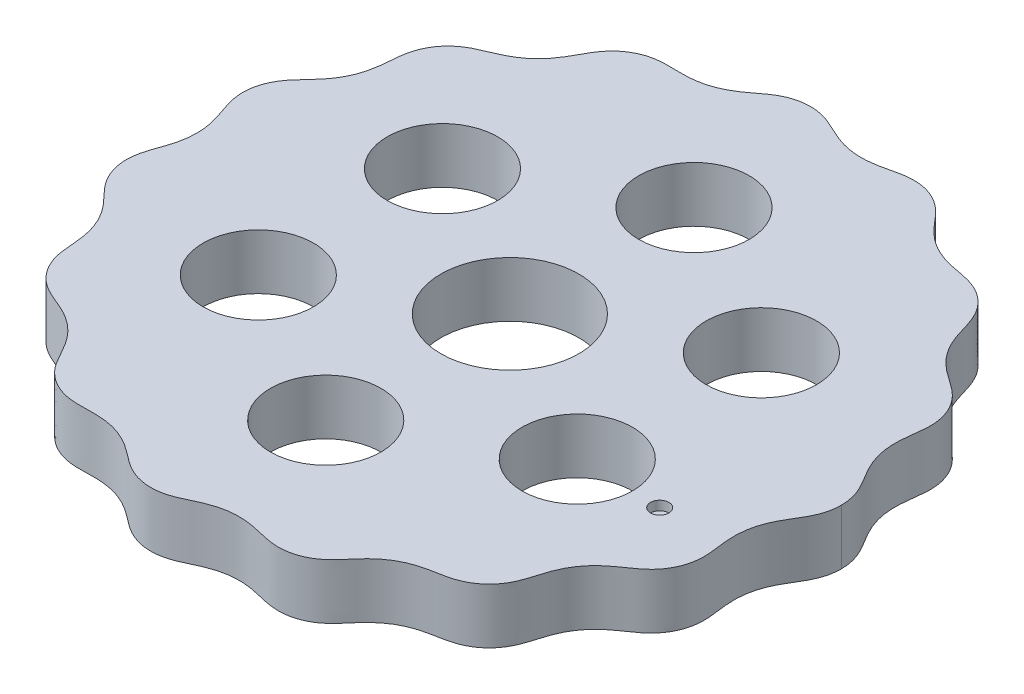
SolidWorks part; units mm, degrees
ref_plane "Front Plane" through (0, 0, 0) normal (0, 0, 1) x (1, 0, 0)
ref_plane "Top Plane" through (0, 0, 0) normal (0, 1, 0) x (1, 0, 0)
ref_plane "Right Plane" through (0, 0, 0) normal (1, 0, 0) x (0, 0, -1)
sketch "Sketch3" plane through (0, 0, 0) normal (0, 1, 0) x (1, 0, 0)
  line L0 (-55, 0) -> (55, 0) construction
  spline S2 degree 4 poles (-35, 0) (-35, -0.0358) (-35.0006, -0.1075) (-35.0034, -0.2568) (-35.0108, -0.4216) (-35.0218, -0.5882) (-35.0365, -0.7567) (-35.0593, -0.9658) (-35.104, -1.2906) (-35.1852, -1.7284) (-35.3211, -2.2743) (-35.5114, -2.8829) (-35.7441, -3.5419) (-35.9992, -4.258) (-36.256, -5.1614) (-36.3903, -6.2748) (-36.277, -7.5121) (-35.8687, -8.6952) (-35.2773, -9.6694) (-34.5543, -10.5199) (-33.7836, -11.2989) (-32.9858, -12.2016) (-32.2646, -13.303) (-31.7377, -14.5286) (-31.4262, -15.8454) (-31.2991, -17.2726) (-31.2161, -18.7053) (-30.8161, -20.1006) (-30.0732, -21.3418) (-29.1744, -22.2504) (-28.1724, -22.8961) (-27.1276, -23.3559) (-26.1086, -23.7587) (-25.0498, -24.278) (-23.9897, -24.9979) (-23.0387, -25.9222) (-22.2349, -27.0329) (-21.57, -28.2819) (-20.9001, -29.5134) (-19.9625, -30.5741) (-18.7952, -31.3663) (-17.5956, -31.8107) (-16.4147, -31.9743) (-15.2812, -31.959) (-14.2035, -31.9175) (-13.0422, -31.968) (-11.7833, -32.2012) (-10.5313, -32.6697) (-9.484, -33.2925) (-8.6483, -33.9206) (-7.824, -34.5602) (-6.9633, -35.1551) (-5.8447, -35.655) (-4.4715, -35.8938) (-3.1871, -35.8055) (-2.026, -35.4617) (-0.9923, -34.9762) (-0.0227, -34.5029) (1.0531, -34.0876) (2.2996, -33.7945) (3.6433, -33.7224) (5.0385, -33.8989) (6.246, -34.2125) (7.2644, -34.4441) (8.3052, -34.5433) (9.3521, -34.4822) (10.5168, -34.1673) (11.6593, -33.5372) (12.5907, -32.7091) (13.341, -31.8149) (14.0543, -30.9824) (14.885, -30.183) (15.9219, -29.4318) (16.9904, -28.9178) (18.0263, -28.6023) (18.918, -28.4136) (19.5788, -28.294) (20.4038, -28.1355) (21.3777, -27.8617) (22.444, -27.3351) (23.4837, -26.4602) (24.2541, -25.4059) (24.7506, -24.2626) (25.0639, -23.1466) (25.3786, -22.114) (25.8131, -21.0649) (26.4604, -19.9607) (27.3438, -18.9326) (28.3229, -18.1436) (29.2182, -17.5418) (30.0287, -16.9727) (30.7971, -16.3286) (31.5499, -15.4136) (32.138, -14.1887) (32.4089, -12.902) (32.389, -11.6377) (32.2136, -10.4744) (32.0853, -9.3852) (32.0701, -8.4106) (32.1519, -7.5639) (32.3146, -6.756) (32.5488, -5.9926) (32.8579, -5.2665) (33.2246, -4.5794) (33.5887, -3.9735) (33.9236, -3.4333) (34.2476, -2.8753) (34.5352, -2.2866) (34.722, -1.7814) (34.8335, -1.3753) (34.8947, -1.0872) (34.9248, -0.9216) (34.9499, -0.7552) (34.9676, -0.6083) (34.9796, -0.4838) (34.9875, -0.3802) (34.9925, -0.2949) (34.9973, -0.1832) (34.9994, -0.0895) (35, -0.0358) (35, 0) knots 0.07237 0.07237 0.07237 0.07237 0.07237 0.073615 0.074861 0.076106 0.077352 0.078597 0.079843 0.082334 0.087049 0.091763 0.096478 0.101193 0.107725 0.114257 0.124215 0.134174 0.144133 0.15093 0.157727 0.167143 0.176558 0.186521 0.196482 0.206428 0.216375 0.228908 0.238867 0.248826 0.258784 0.266347 0.27391 0.282559 0.291208 0.301173 0.311645 0.3216 0.331555 0.343059 0.353018 0.362977 0.372935 0.380513 0.388091 0.396475 0.404859 0.414823 0.425824 0.43578 0.440758 0.445737 0.45671 0.466668 0.476627 0.486585 0.494428 0.502271 0.510391 0.51851 0.528475 0.540003 0.54996 0.559918 0.565389 0.570861 0.580819 0.590778 0.600736 0.609095 0.617453 0.625308 0.633162 0.643126 0.655188 0.660155 0.665121 0.670088 0.675054 0.685012 0.69497 0.704929 0.714887 0.72326 0.731632 0.739222 0.746812 0.756777 0.769366 0.779036 0.78387 0.788705 0.798662 0.808621 0.81858 0.828538 0.837175 0.845812 0.853389 0.860965 0.865947 0.870929 0.877739 0.88455 0.889251 0.893953 0.898654 0.903356 0.908335 0.913314 0.914559 0.915803 0.917048 0.918293 0.919538 0.92016 0.920783 0.921405 0.922028 0.923272 0.923272 0.923272 0.923272 0.923272
  spline S3 degree 4 poles (-35, 0) (-35, 0.0358) (-35.0006, 0.1075) (-35.0034, 0.2568) (-35.0108, 0.4216) (-35.0218, 0.5882) (-35.0365, 0.7567) (-35.0593, 0.9658) (-35.104, 1.2906) (-35.1852, 1.7284) (-35.3211, 2.2743) (-35.5114, 2.8829) (-35.7441, 3.5419) (-35.9992, 4.258) (-36.256, 5.1614) (-36.3903, 6.2748) (-36.277, 7.5121) (-35.8687, 8.6952) (-35.2773, 9.6694) (-34.5543, 10.5199) (-33.7836, 11.2989) (-32.9858, 12.2016) (-32.2646, 13.303) (-31.7377, 14.5286) (-31.4262, 15.8454) (-31.2991, 17.2726) (-31.2161, 18.7053) (-30.8161, 20.1006) (-30.0732, 21.3418) (-29.1744, 22.2504) (-28.1724, 22.8961) (-27.1276, 23.3559) (-26.1086, 23.7587) (-25.0498, 24.278) (-23.9897, 24.9979) (-23.0387, 25.9222) (-22.2349, 27.0329) (-21.57, 28.2819) (-20.9001, 29.5134) (-19.9625, 30.5741) (-18.7952, 31.3663) (-17.5956, 31.8107) (-16.4147, 31.9743) (-15.2812, 31.959) (-14.2035, 31.9175) (-13.0422, 31.968) (-11.7833, 32.2012) (-10.5313, 32.6697) (-9.484, 33.2925) (-8.6483, 33.9206) (-7.824, 34.5602) (-6.9633, 35.1551) (-5.8447, 35.655) (-4.4715, 35.8938) (-3.1871, 35.8055) (-2.026, 35.4617) (-0.9923, 34.9762) (-0.0227, 34.5029) (1.0531, 34.0876) (2.2996, 33.7945) (3.6433, 33.7224) (5.0385, 33.8989) (6.246, 34.2125) (7.2644, 34.4441) (8.3052, 34.5433) (9.3521, 34.4822) (10.5168, 34.1673) (11.6593, 33.5372) (12.5907, 32.7091) (13.341, 31.8149) (14.0543, 30.9824) (14.885, 30.183) (15.9219, 29.4318) (16.9904, 28.9178) (18.0263, 28.6023) (18.918, 28.4136) (19.5788, 28.294) (20.4038, 28.1355) (21.3777, 27.8617) (22.444, 27.3351) (23.4837, 26.4602) (24.2541, 25.4059) (24.7506, 24.2626) (25.0639, 23.1466) (25.3786, 22.114) (25.8131, 21.0649) (26.4604, 19.9607) (27.3438, 18.9326) (28.3229, 18.1436) (29.2182, 17.5418) (30.0287, 16.9727) (30.7971, 16.3286) (31.5499, 15.4136) (32.138, 14.1887) (32.4089, 12.902) (32.389, 11.6377) (32.2136, 10.4744) (32.0853, 9.3852) (32.0701, 8.4106) (32.1519, 7.5639) (32.3146, 6.756) (32.5488, 5.9926) (32.8579, 5.2665) (33.2246, 4.5794) (33.5887, 3.9735) (33.9236, 3.4333) (34.2476, 2.8753) (34.5352, 2.2866) (34.722, 1.7814) (34.8335, 1.3753) (34.8947, 1.0872) (34.9248, 0.9216) (34.9499, 0.7552) (34.9676, 0.6083) (34.9796, 0.4838) (34.9875, 0.3802) (34.9925, 0.2949) (34.9973, 0.1832) (34.9994, 0.0895) (35, 0.0358) (35, 0) knots 0.07237 0.07237 0.07237 0.07237 0.07237 0.073615 0.074861 0.076106 0.077352 0.078597 0.079843 0.082334 0.087049 0.091763 0.096478 0.101193 0.107725 0.114257 0.124215 0.134174 0.144133 0.15093 0.157727 0.167143 0.176558 0.186521 0.196482 0.206428 0.216375 0.228908 0.238867 0.248826 0.258784 0.266347 0.27391 0.282559 0.291208 0.301173 0.311645 0.3216 0.331555 0.343059 0.353018 0.362977 0.372935 0.380513 0.388091 0.396475 0.404859 0.414823 0.425824 0.43578 0.440758 0.445737 0.45671 0.466668 0.476627 0.486585 0.494428 0.502271 0.510391 0.51851 0.528475 0.540003 0.54996 0.559918 0.565389 0.570861 0.580819 0.590778 0.600736 0.609095 0.617453 0.625308 0.633162 0.643126 0.655188 0.660155 0.665121 0.670088 0.675054 0.685012 0.69497 0.704929 0.714887 0.72326 0.731632 0.739222 0.746812 0.756777 0.769366 0.779036 0.78387 0.788705 0.798662 0.808621 0.81858 0.828538 0.837175 0.845812 0.853389 0.860965 0.865947 0.870929 0.877739 0.88455 0.889251 0.893953 0.898654 0.903356 0.908335 0.913314 0.914559 0.915803 0.917048 0.918293 0.919538 0.92016 0.920783 0.921405 0.922028 0.923272 0.923272 0.923272 0.923272 0.923272
extrude "Boss-Extrude1" add sketch "Sketch3" along normal blind 6
sketch "Sketch4" plane through (0, 6, 0) normal (0, 1, 0) x (1, 0, 0)
  circle A0 centre (-1, 0) radius 7.5
  circle A1 centre (-1, 0) radius 20 construction
  circle A2 centre (-1, 20) radius 6
  circle A3 centre (16.3205, 10) radius 6
  circle A4 centre (16.3205, -10) radius 6
  circle A5 centre (-1, -20) radius 6
  circle A6 centre (-18.3205, -10) radius 6
  circle A7 centre (-18.3205, 10) radius 6
  point P19 (-1, 0)
  dimension "D1" = 15
  dimension "D2" = 40
  dimension "D3" = 12
  dimension "D5" = 1
  dimension "D4" = 6
extrude "Cut-Extrude1" cut sketch "Sketch4" against normal through all
sketch "Sketch5" plane through (0, 6, 0) normal (0, 1, 0) x (1, 0, 0)
  circle A0 centre (25.3715, -10.0924) radius 1
  dimension "D1" = 2
extrude "Cut-Extrude2" cut sketch "Sketch5" against normal blind 1 contours A0
equation "\"R_SUN\"= 40"
equation "\"R_ROLL\"= 5"
equation "\"GRATIO\"= 15"
equation "\"RHO\"= 1"
